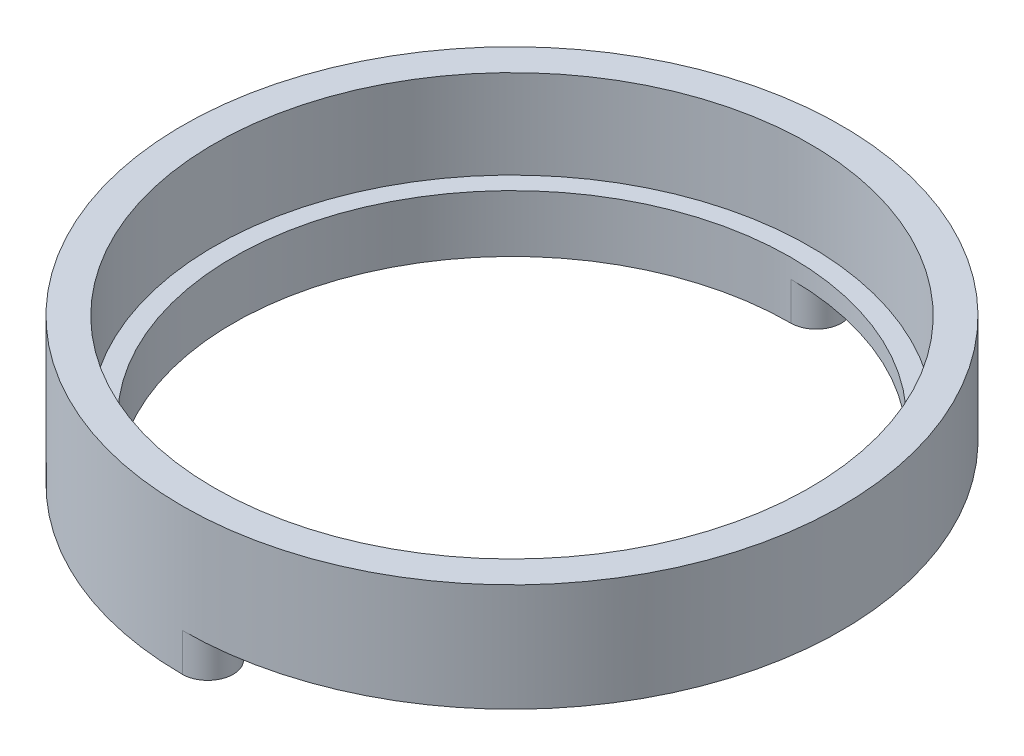
SolidWorks part; units mm, degrees
material "1060 Alloy"
ref_plane "Front Plane" through (0, 0, 0) normal (0, 0, 1) x (1, 0, 0)
ref_plane "Top Plane" through (0, 0, 0) normal (0, 1, 0) x (1, 0, 0)
ref_plane "Right Plane" through (0, 0, 0) normal (1, 0, 0) x (0, 0, -1)
sketch "Sketch1" plane through (0, 0, 0) normal (0, 1, 0) x (1, 0, 0)
  circle A0 centre (0, 0) radius 22
  circle A1 centre (0, 0) radius 23.5
  dimension "D1" = 44
  dimension "D2" = 47
extrude "Boss-Extrude1" add sketch "Sketch1" along normal blind 1.5
sketch "Sketch2" plane through (0, 0, 0) normal (0, 1, 0) x (1, 0, 0)
  circle A0 centre (0, 0) radius 23.5
  circle A1 centre (0, 0) radius 26
  dimension "D1" = 47
  dimension "D2" = 52
extrude "Boss-Extrude2" add sketch "Sketch2" along normal blind 8.5
sketch "Sketch3" plane through (0, 0, 0) normal (0, -1, 0) x (1, 0, 0)
  line L0 (0, -44.7868) -> (0, 44.7868) construction
  arc A0 (0, 24) -> (0, -24) centre (0, 0) ccw construction
  arc A1 (0, 26) -> (0, -26) centre (0, 0) ccw
  arc A2 (0, 22) -> (0, -22) centre (0, 0) ccw
  arc A3 (0, 22) -> (0, 26) centre (0, 24) ccw
  arc A4 (0, -26) -> (0, -22) centre (0, -24) ccw
  point P6 (-24, 0)
  dimension "D3" = 24
  dimension "D1" = 4
  dimension "D2" = 180
extrude "Boss-Extrude3" add sketch "Sketch3" along normal blind 3
